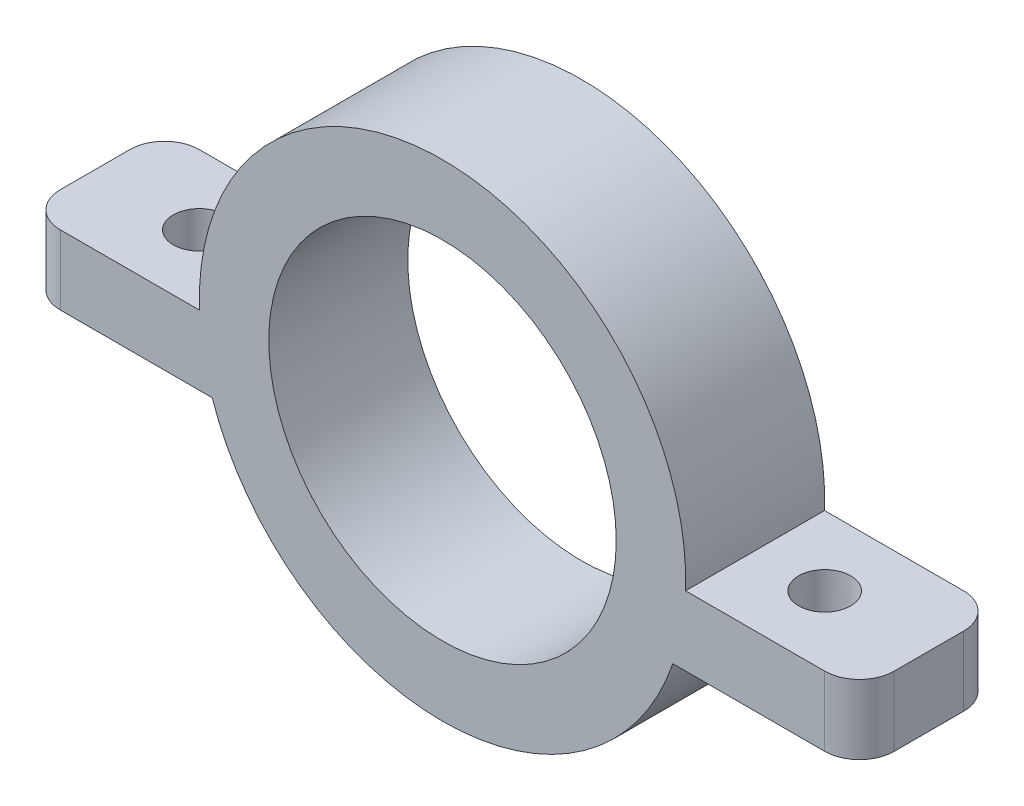
SolidWorks part; units mm, degrees
ref_plane "Alzado" through (0, 0, 0) normal (0, 0, 1) x (1, 0, 0)
ref_plane "Planta" through (0, 0, 0) normal (0, 1, 0) x (1, 0, 0)
ref_plane "Vista lateral" through (0, 0, 0) normal (1, 0, 0) x (0, 0, -1)
sketch "Croquis1" plane through (0, 0, 0) normal (0, 0, 1) x (1, 0, 0)
  line L0 (-24, -0.5) -> (-13.9911, -0.5)
  line L1 (-24, -4.5) -> (-13.2571, -4.5)
  line L2 (24, -0.5) -> (13.9911, -0.5)
  line L3 (-24, -0.5) -> (-24, -4.5)
  line L4 (24, -4.5) -> (13.2571, -4.5)
  line L5 (0, -10) -> (0, 10) construction
  line L7 (24, -0.5) -> (24, -4.5)
  line L9 (-24, -4.5) -> (-24, -12.5) construction
  line L10 (0, 0) -> (0, -17.5) construction
  circle A0 centre (0, 0) radius 10
  arc A1 (-13.9911, -0.5) -> (13.9911, -0.5) centre (0, 0) cw
  arc A2 (-13.2571, -4.5) -> (13.2571, -4.5) centre (0, 0) ccw
  dimension "D1" = 20
  dimension "D2" = 0.5
  dimension "D5" = 14
  dimension "D6" = 24
  dimension "D4" = 14
  dimension "D3" = 4
extrude "Saliente-Extruir1" add sketch "Croquis1" along normal blind 8 contours L3 L1 A2 L4 L7 L2 A1 L0
sketch "Croquis2" plane through (0, 0, 8) normal (0, 0, 1) x (1, 0, 0)
  circle A0 centre (0, 0) radius 10
  dimension "D1" = 20
extrude "Cortar-Extruir1" cut sketch "Croquis2" against normal through all
fillet "Redondeo1" radius 2 4 edges at (24, -2.5, 8) (24, -2.5, 0) (-24, -2.5, 0) (-24, -2.5, 8)
sketch "Croquis3" plane through (0, -0.5, 0) normal (0, 1, 0) x (1, 0, 0)
  line L0 (-22, -8) -> (-13.9911, 0) construction
  line L1 (22, 0) -> (13.9911, -8) construction
  circle A0 centre (-17.9955, -4) radius 1.5
  circle A1 centre (17.9955, -4) radius 1.5
  dimension "D1" = 3
  dimension "D2" = 3
extrude "Cortar-Extruir2" cut sketch "Croquis3" against normal through all
